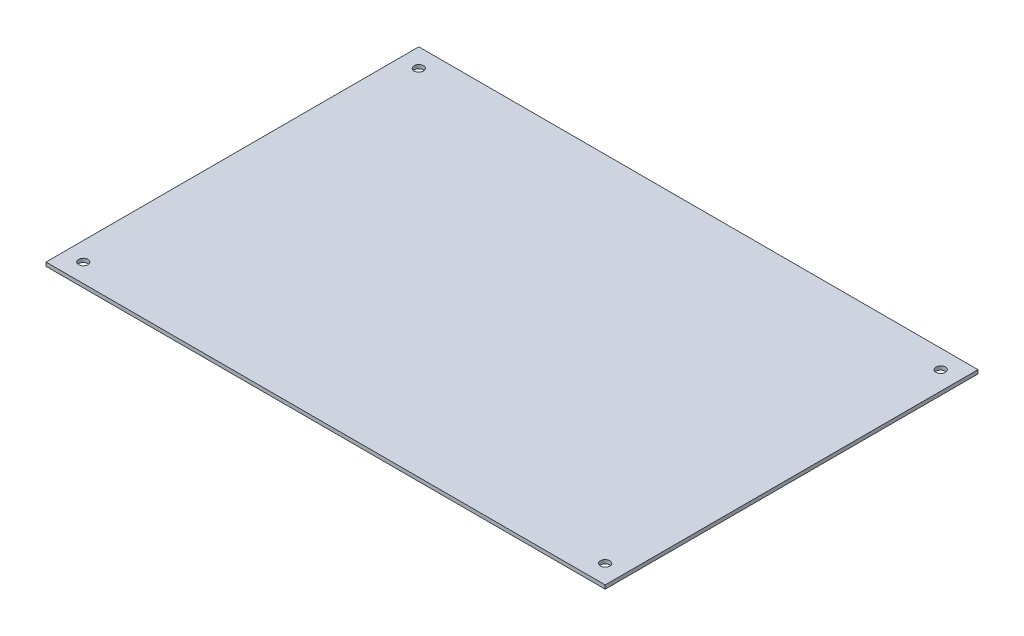
SolidWorks part; units mm, degrees
material "ABS"
ref_plane "Plano frontal" through (0, 0, 0) normal (0, 0, 1) x (1, 0, 0)
ref_plane "Plano superior" through (0, 0, 0) normal (0, 1, 0) x (1, 0, 0)
ref_plane "Plano direito" through (0, 0, 0) normal (1, 0, 0) x (0, 0, -1)
sketch "Esboço1" plane through (0, 0, 0) normal (0, 1, 0) x (1, 0, 0)
  line L0 (-36.9446, 34.7359) -> (-26.9446, 34.7359)
  line L1 (-36.9446, 34.7359) -> (263.0554, 34.7359)
  line L2 (-36.9446, 34.7359) -> (-36.9446, -165.2641)
  line L3 (-36.9446, -165.2641) -> (263.0554, -165.2641)
  line L4 (263.0554, 34.7359) -> (263.0554, -165.2641)
  line L6 (263.0554, 34.7359) -> (253.0554, 34.7359)
  line L8 (263.0554, -165.2641) -> (253.0554, -165.2641)
  line L10 (-36.9446, -165.2641) -> (-26.9446, -165.2641)
  circle A0 centre (-26.9446, 24.7359) radius 2.5
  circle A1 centre (253.0554, 24.7359) radius 2.5
  circle A2 centre (253.0554, -155.2641) radius 2.5
  circle A3 centre (-26.9446, -155.2641) radius 2.5
  dimension "D11" = 5
  dimension "D12" = 5
  dimension "D13" = 5
  dimension "D14" = 5
  dimension "D1" = 300
  dimension "D2" = 200
  dimension "D3" = 10
  dimension "D4" = 10
  dimension "D5" = 10
  dimension "D6" = 10
  dimension "D7" = 10
  dimension "D8" = 10
  dimension "D9" = 10
  dimension "D10" = 10
extrude "Ressalto-extrusão1" add sketch "Esboço1" along normal blind 2 contours L4 L1 L0 L2 L3 A3 A2 A1 A0
